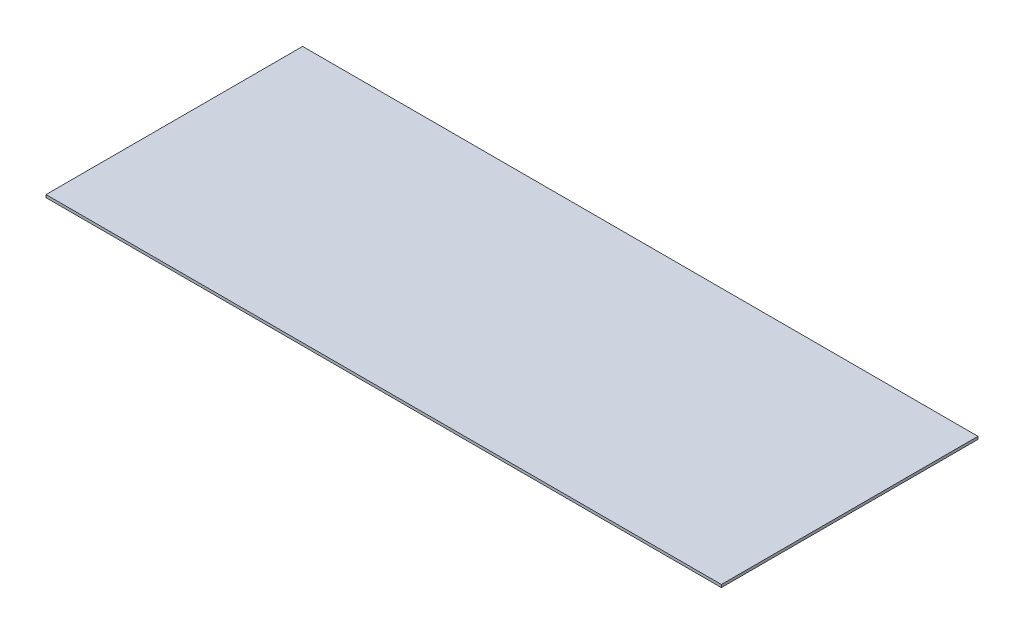
SolidWorks part; units mm, degrees
ref_plane "Front Plane" through (0, 0, 0) normal (0, 0, 1) x (1, 0, 0)
ref_plane "Top Plane" through (0, 0, 0) normal (0, 1, 0) x (1, 0, 0)
ref_plane "Right Plane" through (0, 0, 0) normal (1, 0, 0) x (0, 0, -1)
sketch "Sketch1" plane through (0, 0, 0) normal (0, 1, 0) x (1, 0, 0)
  line L1 (-176.5123, 119.0926) -> (323.4877, 119.0926)
  line L2 (-176.5123, 119.0926) -> (-176.5123, -70.9074)
  line L3 (-176.5123, -70.9074) -> (323.4877, -70.9074)
  line L4 (323.4877, 119.0926) -> (323.4877, -70.9074)
  dimension "D1" = 500
  dimension "D2" = 190
extrude "Boss-Extrude1" add sketch "Sketch1" along normal blind 2
